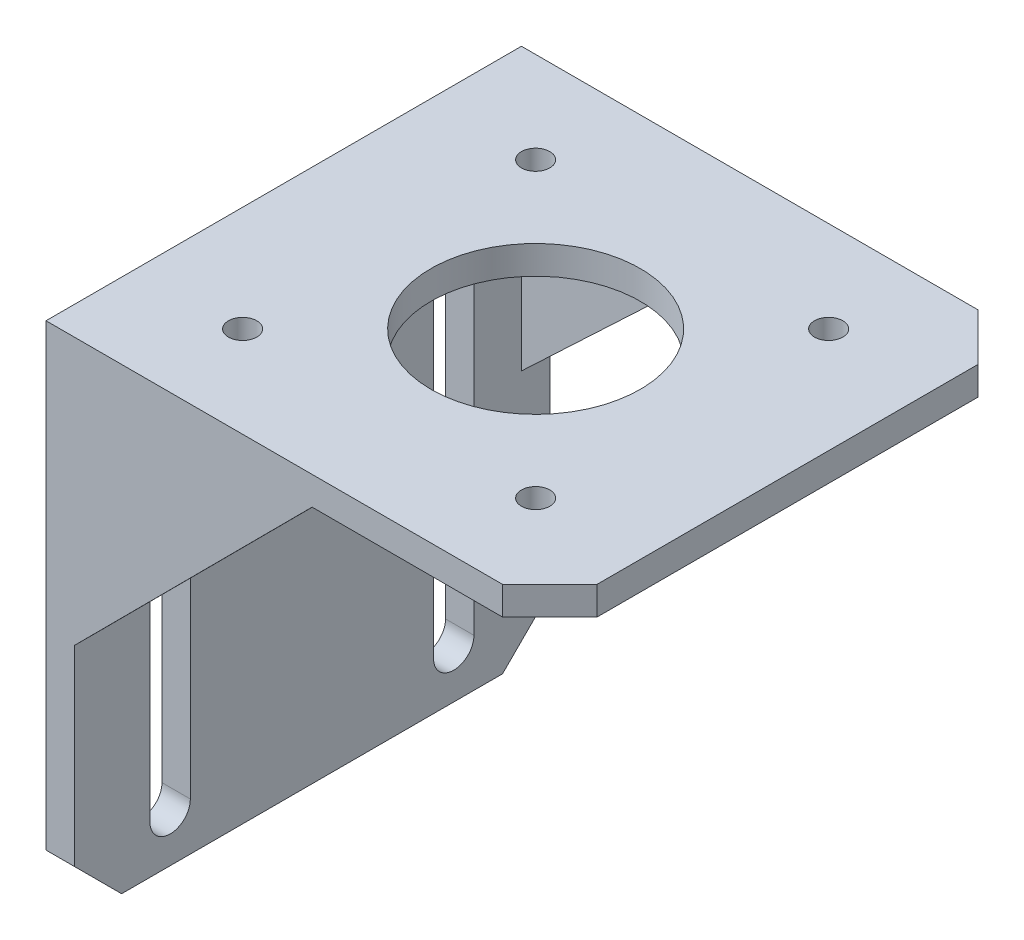
SolidWorks part; units mm, degrees
ref_plane "Front Plane" through (0, 0, 0) normal (0, 0, 1) x (1, 0, 0)
ref_plane "Top Plane" through (0, 0, 0) normal (0, 1, 0) x (1, 0, 0)
ref_plane "Right Plane" through (0, 0, 0) normal (1, 0, 0) x (0, 0, -1)
sketch "Sketch1" plane through (0, 0, 0) normal (1, 0, 0) x (0, 0, -1)
  line L1 (-14.9989, 23.6362) -> (35.3011, 23.6362)
  line L2 (-14.9989, 23.6362) -> (-14.9989, -29.8638)
  line L3 (-14.9989, -29.8638) -> (35.3011, -29.8638)
  line L4 (35.3011, 23.6362) -> (35.3011, -29.8638)
  line L5 (-6.9989, -24.8184) -> (-6.9989, 18.3152)
  line L6 (27.2711, 18.3152) -> (27.2711, -24.8184)
  line L7 (-2.7289, 18.3152) -> (-2.7289, -24.8184)
  line L10 (23.0011, 18.3152) -> (23.0011, -24.8184)
  arc A0 (-6.9989, 18.3152) -> (-2.7289, 18.3152) centre (-4.8639, 18.3152) cw
  arc A1 (-6.9989, -24.8184) -> (-2.7289, -24.8184) centre (-4.8639, -24.8184) ccw
  arc A2 (27.2711, 18.3152) -> (23.0011, 18.3152) centre (25.1361, 18.3152) ccw
  arc A3 (23.0011, -24.8184) -> (27.2711, -24.8184) centre (25.1361, -24.8184) ccw
  point P6 (-14.9989, -24.8184)
extrude "Boss-Extrude1" add sketch "Sketch1" along normal blind 3
sketch "Sketch3" plane through (3, 0, 0) normal (1, 0, 0) x (0, 0, -1)
  line L0 (35.3011, -29.8638) -> (35.3011, 23.6362) construction
  line L1 (-14.9989, 23.6362) -> (35.3011, 23.6362)
  line L2 (-14.9989, 23.6362) -> (-14.9989, 20.6362)
  line L3 (-14.9989, 20.6362) -> (35.3011, 20.6362)
  line L4 (35.3011, 23.6362) -> (35.3011, 20.6362)
extrude "Boss-Extrude3" add sketch "Sketch3" along normal blind 50.3
sketch "Sketch7" plane through (0, 0, -35.3011) normal (0, 0, -1) x (-1, 0, 0)
  line L0 (-3, 20.6362) -> (-28.15, 20.6362)
  line L1 (-53.3, 20.6362) -> (-3, 20.6362) construction
  line L2 (-28.15, 20.6362) -> (-3, -3.1138)
  line L3 (-3, -29.8638) -> (-3, 20.6362) construction
  line L10 (0, -29.8638) -> (0, 23.6362)
  line L11 (0, 23.6362) -> (-53.3, 23.6362)
  line L12 (-53.3, 23.6362) -> (-53.3, 20.6362)
  line L13 (-53.3, 20.6362) -> (-3, 20.6362)
  line L14 (-3, 20.6362) -> (-3, -29.8638)
  line L15 (-3, -29.8638) -> (0, -29.8638)
  line L20 (-3, 20.6362) -> (-3, -3.1138)
  dimension "D1" = 0
sketch "Sketch11" plane through (0, 0, 14.9989) normal (0, 0, 1) x (1, 0, 0)
  line L0 (3, 20.6362) -> (3, -4.6138)
  line L1 (3, 20.6362) -> (3, -29.8638) construction
  line L2 (3, -4.6138) -> (28.15, 20.6362)
  line L3 (53.3, 20.6362) -> (3, 20.6362) construction
  line L4 (28.15, 20.6362) -> (3, 20.6362)
extrude "Boss-Extrude6" add sketch "Sketch11" against normal blind 3
extrude "Boss-Extrude7" add sketch "Sketch7" against normal blind 3 contours L2 L20 L0
sketch "Sketch12" plane through (0, 23.6362, 0) normal (0, 1, 0) x (1, 0, 0)
  circle A0 centre (42.15, 25.6511) radius 1.5
  circle A1 centre (42.15, -5.3489) radius 1.5
  circle A2 centre (11.15, 25.6511) radius 1.5
  circle A3 centre (11.15, -5.3489) radius 1.5
  circle A4 centre (26.65, 10.1511) radius 11.075
  point P4 (26.65, 10.1511)
extrude "Cut-Extrude1" cut sketch "Sketch12" against normal blind 3
chamfer "Chamfer2" distance 5 angle 45 1 edges at (53.3, 22.1362, -35.3011)
chamfer "Chamfer3" distance 5 angle 45 1 edges at (53.3, 22.1362, 14.9989)
chamfer "Chamfer4" distance 5 angle 45 1 edges at (1.5, -29.8638, 14.9989)
chamfer "Chamfer5" distance 5 angle 45 1 edges at (1.5, -29.8638, -35.3011)
